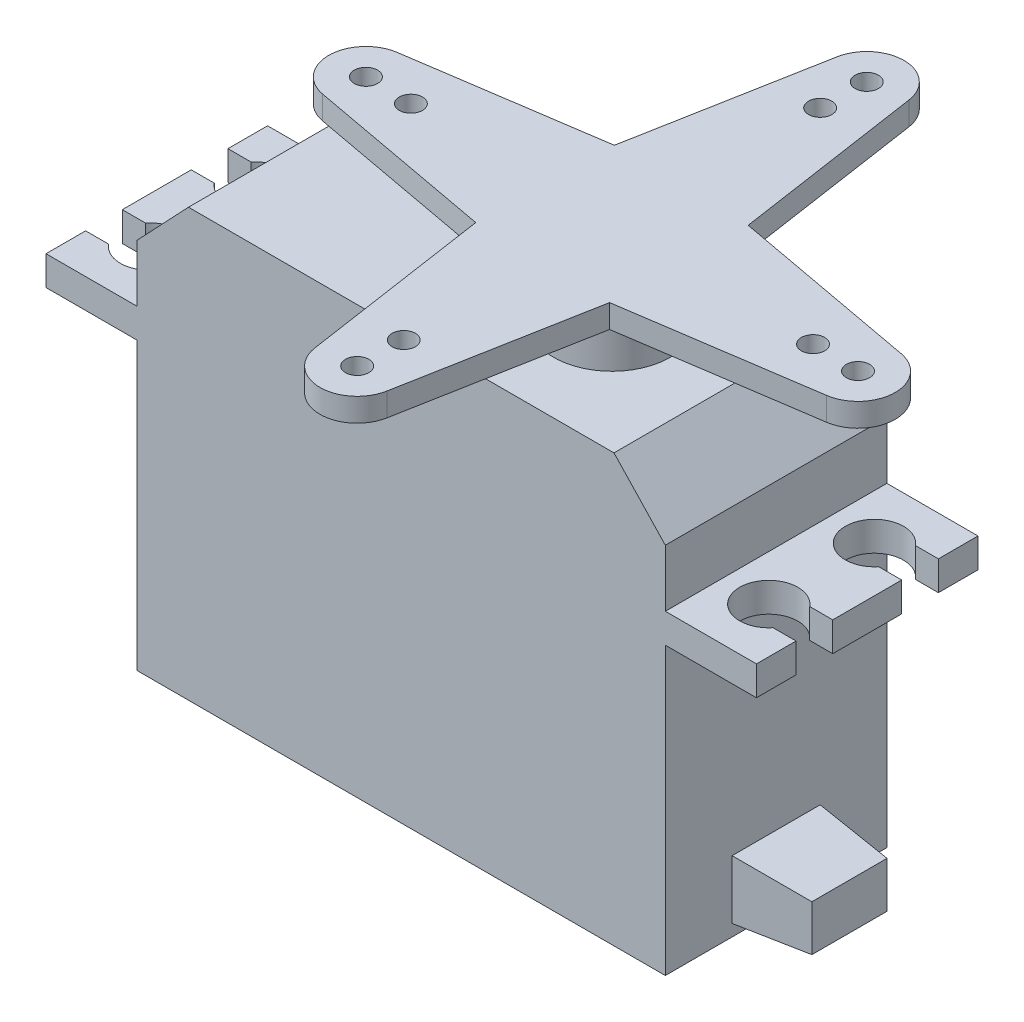
SolidWorks part; units mm, degrees
ref_plane "Front Plane" through (0, 0, 0) normal (0, 0, 1) x (1, 0, 0)
ref_plane "Top Plane" through (0, 0, 0) normal (0, 1, 0) x (1, 0, 0)
ref_plane "Right Plane" through (0, 0, 0) normal (1, 0, 0) x (0, 0, -1)
sketch "Sketch1" plane through (0, 0, 0) normal (0, 0, 1) x (1, 0, 0)
  line L0 (-24.2094, 2) -> (-24.2094, 0)
  line L1 (-24.2094, 0) -> (-18, 0)
  line L2 (-18, 0) -> (-18, -19.5)
  line L3 (-18, -19.5) -> (18, -19.5)
  line L4 (0, -19.5) -> (0, 9.6) construction
  line L5 (24.2094, 2) -> (18, 2)
  line L6 (18, 0) -> (18, -19.5)
  line L7 (24.2094, 0) -> (18, 0)
  line L8 (24.2094, 2) -> (24.2094, 0)
  line L9 (-18, 2) -> (-18, 5.9)
  line L10 (-18, 5.9) -> (-14.5, 9.6)
  line L11 (-14.5, 9.6) -> (14.5, 9.6)
  line L12 (18, 5.9) -> (14.5, 9.6)
  line L13 (18, 2) -> (18, 5.9)
  line L14 (-18, 2) -> (-24.2094, 2)
  point P16 (0, 9.6)
  dimension "D1" = 36
  dimension "D2" = 19.5
  dimension "D3" = 2
  dimension "D4" = 48.4187
  dimension "D5" = 7.6
  dimension "D6" = 3.9
  dimension "D7" = 3.5
extrude "Boss-Extrude1" add sketch "Sketch1" along normal mid plane 15.1
sketch "Sketch2" plane through (0, 2, 0) normal (0, 1, 0) x (1, 0, 0)
  line L0 (-24.2094, -2.35) -> (-22.6412, -2.35)
  line L1 (-24.2094, -7.55) -> (-24.2094, 7.55) construction
  line L2 (-24.2094, -4.85) -> (-22.6412, -4.85)
  line L3 (-24.2094, -2.35) -> (-24.2094, -4.85)
  line L4 (-12.4332, 0) -> (0, 0) construction
  line L5 (0, 0) -> (0, -6.0457) construction
  line L6 (24.2094, -2.35) -> (24.2094, -4.85)
  line L7 (24.2094, -4.85) -> (22.6412, -4.85)
  line L8 (24.2094, -2.35) -> (22.6412, -2.35)
  line L9 (24.2094, 2.35) -> (22.6412, 2.35)
  line L10 (24.2094, 4.85) -> (22.6412, 4.85)
  line L11 (24.2094, 2.35) -> (24.2094, 4.85)
  line L12 (-24.2094, 2.35) -> (-24.2094, 4.85)
  line L13 (-24.2094, 4.85) -> (-22.6412, 4.85)
  line L14 (-24.2094, 2.35) -> (-22.6412, 2.35)
  arc A0 (-22.6412, -4.85) -> (-22.6412, -2.35) centre (-21.1, -3.6) ccw
  arc A1 (22.6412, -4.85) -> (22.6412, -2.35) centre (21.1, -3.6) cw
  arc A2 (22.6412, 4.85) -> (22.6412, 2.35) centre (21.1, 3.6) ccw
  arc A3 (-22.6412, 4.85) -> (-22.6412, 2.35) centre (-21.1, 3.6) cw
  dimension "D1" = 7.2
  dimension "D3" = 1.9844
  dimension "D4" = 42.2
  dimension "D2" = 2.5
extrude "Cut-Extrude1" cut sketch "Sketch2" against normal up to next
sketch "Sketch3" plane through (0, 2, 0) normal (0, 1, 0) x (1, 0, 0)
  line L0 (0, 0) -> (6.8125, 0) construction
  circle A0 centre (6.8125, 0) radius 3.9688
  arc A1 (22.6412, -2.35) -> (22.6412, -4.85) centre (21.1, -3.6) ccw construction
  dimension "D1" = 7.9375
  dimension "D2" = 14.2875
extrude "Boss-Extrude2" add sketch "Sketch3" along normal blind 11.9062
sketch "Sketch4" plane through (0, 13.9063, 0) normal (0, 1, 0) x (1, 0, 0)
  line L0 (2.1692, 4.6433) -> (-10.6747, 2.5)
  line L1 (-10.6747, -2.5) -> (2.1692, -4.6433)
  line L2 (11.4558, 4.6433) -> (9.3125, 17.4872)
  line L3 (4.3125, 17.4872) -> (2.1692, 4.6433)
  line L4 (11.4558, -4.6433) -> (24.2997, -2.5)
  line L5 (24.2997, 2.5) -> (11.4558, 4.6433)
  line L6 (2.1692, -4.6433) -> (4.3125, -17.4872)
  line L7 (9.3125, -17.4872) -> (11.4558, -4.6433)
  line L8 (-10.2575, 0) -> (6.8125, 0) construction
  line L9 (-0.1875, 4.25) -> (-0.1875, -4.25) construction
  line L10 (13.8125, 4.25) -> (13.8125, -4.25) construction
  arc A0 (-10.6747, 2.5) -> (-10.6747, -2.5) centre (-10.2575, 0) ccw
  arc A1 (9.3125, 17.4872) -> (4.3125, 17.4872) centre (6.8125, 17.07) ccw
  arc A2 (24.2997, -2.5) -> (24.2997, 2.5) centre (23.8825, 0) ccw
  arc A3 (4.3125, -17.4872) -> (9.3125, -17.4872) centre (6.8125, -17.07) ccw
  circle A4 centre (-10.2575, 0) radius 0.7937
  circle A5 centre (6.8125, 17.07) radius 0.7938
  circle A6 centre (23.8825, 0) radius 0.7937
  circle A7 centre (6.8125, -17.07) radius 0.7938
  circle A8 centre (-7.1375, 0) radius 0.7938
  circle A9 centre (6.8125, 13.95) radius 0.7938
  circle A10 centre (20.7625, 0) radius 0.7937
  circle A11 centre (6.8125, -13.95) radius 0.7938
  point P23 (6.8125, 0)
  dimension "D4" = 34.14
  dimension "D5" = 1.5875
  dimension "D6" = 27.9
  dimension "D2" = 5
  dimension "D3" = 14
  dimension "D7" = 8.5
  dimension "D1" = 4
extrude "Boss-Extrude3" add sketch "Sketch4" along normal blind 1.5875 separate body
sketch "Sketch5" plane through (18, 0, 0) normal (1, 0, 0) x (0, 0, -1)
  line L0 (0, -14.7) -> (0, 0) construction
  line L1 (-3, -14.7) -> (3, -14.7)
  line L2 (-3, -14.7) -> (-3, -18.7)
  line L3 (-3, -18.7) -> (3, -18.7)
  line L4 (3, -14.7) -> (3, -18.7)
  line L5 (-7.55, -19.5) -> (7.55, -19.5) construction
  dimension "D1" = 6
  dimension "D2" = 4
  dimension "D3" = 0.8
extrude "Boss-Extrude4" add sketch "Sketch5" along normal blind 5 draft 5
move or copy body "Body-Move/Copy1" bodies to move or copy 104 copy no rotation origin (6.8125, 0, 0) rotation axis (0, -1, 0) rotation angle 1
